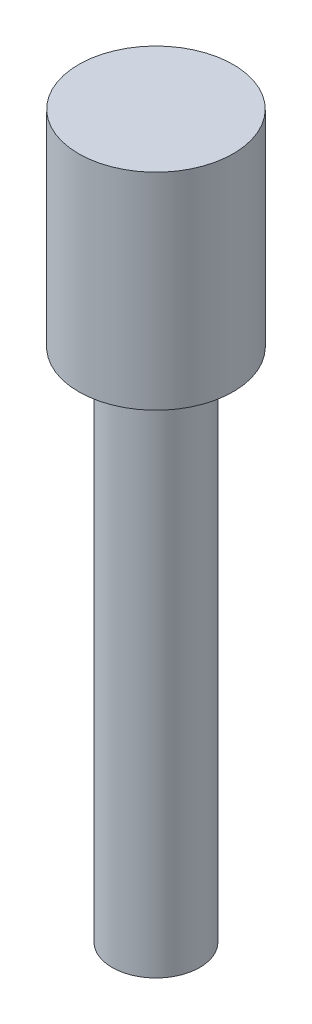
SolidWorks part; units mm, degrees
material "AISI 316 Stainless Steel Sheet (SS)"
ref_plane "Front Plane" through (0, 0, 0) normal (0, 0, 1) x (1, 0, 0)
ref_plane "Top Plane" through (0, 0, 0) normal (0, 1, 0) x (1, 0, 0)
ref_plane "Right Plane" through (0, 0, 0) normal (1, 0, 0) x (0, 0, -1)
sketch "Sketch1" plane through (0, 0, 0) normal (0, 1, 0) x (1, 0, 0)
  circle A0 centre (0, 0) radius 10.795
  dimension "D1" = 21.59
extrude "Boss-Extrude1" add sketch "Sketch1" along normal blind 127
sketch "Sketch2" plane through (0, 127, 0) normal (0, 1, 0) x (1, 0, 0)
  circle A0 centre (0, 0) radius 19.05
  dimension "D1" = 38.1
extrude "Boss-Extrude2" add sketch "Sketch2" along normal blind 50.8
